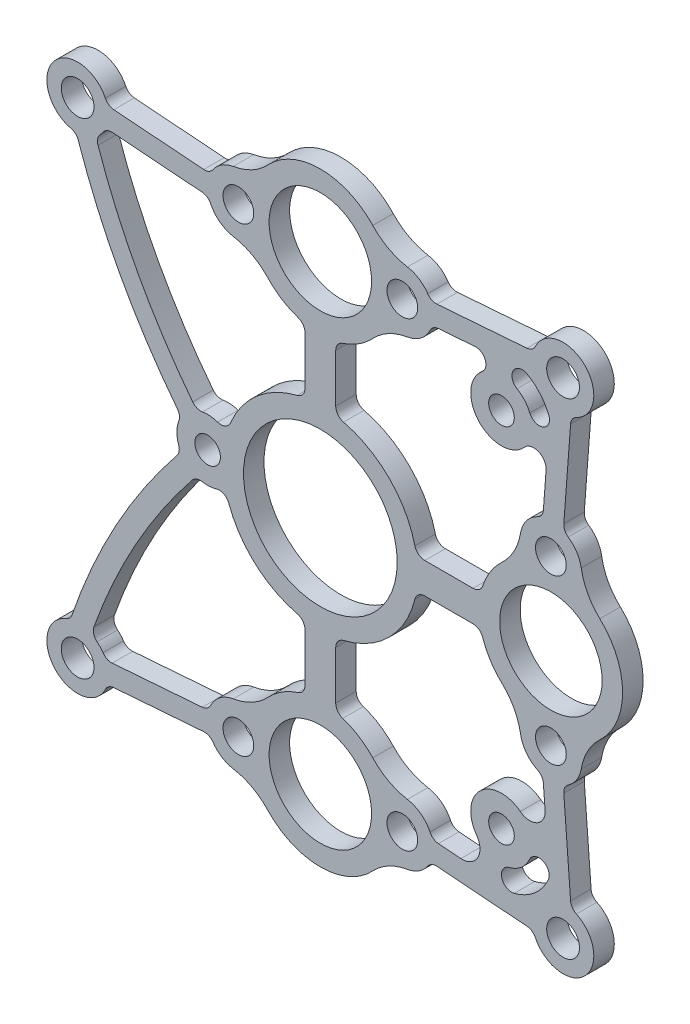
SolidWorks part; units mm, degrees
material "A2017"
ref_plane "正面" through (0, 0, 0) normal (0, 0, 1) x (1, 0, 0)
ref_plane "平面" through (0, 0, 0) normal (0, 1, 0) x (1, 0, 0)
ref_plane "右側面" through (0, 0, 0) normal (1, 0, 0) x (0, 0, -1)
sketch "ｽｹｯﾁ1" plane through (0, 0, 0) normal (0, 0, 1) x (1, 0, 0)
  line L0 (0, 29.5) -> (0, 22.5) construction
  line L1 (-8, 22.5) -> (8, 22.5) construction
  line L2 (29.5, 0) -> (22.5, 0) construction
  line L3 (22.5, 8) -> (22.5, -8) construction
  line L4 (0, -29.5) -> (0, -22.5) construction
  line L5 (8, -22.5) -> (-8, -22.5) construction
  line L6 (-29.5, 0) -> (-22.5, 0) construction
  line L7 (-22.5, -8) -> (-22.5, 8) construction
  circle A1 centre (23.6881, 23.6881) radius 3
  circle A2 centre (23.6881, 23.6881) radius 3
  circle A3 centre (22.5, 0) radius 5
  circle A5 centre (22.5, -8) radius 1.5
  circle A7 centre (0, 22.5) radius 5
  circle A8 centre (0, 22.5) radius 5
  circle A9 centre (0, 0) radius 7.5
  circle A10 centre (0, 0) radius 7.5
  circle A11 centre (8, 22.5) radius 1.5
  circle A12 centre (8, 22.5) radius 1.5
  circle A13 centre (-8, 22.5) radius 1.5
  circle A14 centre (-8, 22.5) radius 1.5
  circle A15 centre (-23.6881, -23.6881) radius 3
  circle A16 centre (-23.6881, -23.6881) radius 3
  circle A17 centre (-23.6881, 23.6881) radius 3
  circle A18 centre (-23.6881, 23.6881) radius 3
  circle A19 centre (23.6881, -23.6881) radius 3
  circle A20 centre (23.6881, -23.6881) radius 3
  circle A21 centre (22.5, 8) radius 1.5
  arc A23 (27.2784, 5.1154) -> (27.2784, -5.1154) centre (22.5, 0) cw
  arc A25 (27.2784, 5.1154) -> (25.458, 8.5) centre (31.3741, 9.5) cw
  arc A27 (27.2784, -5.1154) -> (25.458, -8.5) centre (31.3741, -9.5) ccw
  circle A42 centre (0, 0) radius 9.5
  circle A43 centre (-23.6881, 23.6881) radius 1.6
  circle A44 centre (-23.6881, -23.6881) radius 1.6
  circle A45 centre (23.6881, -23.6881) radius 1.6
  circle A46 centre (23.6881, 23.6881) radius 1.6
  circle A47 centre (-8, 22.5) radius 3 construction
  circle A48 centre (0, 22.5) radius 7 construction
  circle A49 centre (8, 22.5) radius 3 construction
  arc A50 (-5.1154, 27.2784) -> (5.1154, 27.2784) centre (0, 22.5) cw
  arc A51 (-5.1154, 27.2784) -> (-8.5, 25.458) centre (-9.5, 31.3741) cw
  arc A52 (5.1154, 27.2784) -> (8.5, 25.458) centre (9.5, 31.3741) ccw
  arc A53 (-8.5, 25.458) -> (-8.5, 19.542) centre (-8, 22.5) ccw
  arc A54 (8.5, 25.458) -> (8.5, 19.542) centre (8, 22.5) cw
  arc A55 (-5.1154, 17.7216) -> (-8.5, 19.542) centre (-9.5, 13.6259) ccw
  arc A56 (-5.1154, 17.7216) -> (5.1154, 17.7216) centre (0, 22.5) ccw
  arc A57 (5.1154, 17.7216) -> (8.5, 19.542) centre (9.5, 13.6259) cw
  arc A58 (25.458, 8.5) -> (19.542, 8.5) centre (22.5, 8) ccw
  arc A59 (25.458, -8.5) -> (19.542, -8.5) centre (22.5, -8) cw
  arc A60 (17.7216, 5.1154) -> (19.542, 8.5) centre (13.6259, 9.5) ccw
  arc A61 (17.7216, 5.1154) -> (17.7216, -5.1154) centre (22.5, 0) ccw
  arc A62 (17.7216, -5.1154) -> (19.542, -8.5) centre (13.6259, -9.5) cw
  circle A63 centre (22.5, 8) radius 3 construction
  circle A64 centre (22.5, 0) radius 7 construction
  circle A65 centre (22.5, -8) radius 3 construction
  circle A66 centre (0, -22.5) radius 5
  circle A67 centre (-8, -22.5) radius 1.5
  circle A68 centre (8, -22.5) radius 1.5
  arc A69 (5.1154, -27.2784) -> (-5.1154, -27.2784) centre (0, -22.5) cw
  arc A70 (5.1154, -27.2784) -> (8.5, -25.458) centre (9.5, -31.3741) cw
  arc A71 (-5.1154, -27.2784) -> (-8.5, -25.458) centre (-9.5, -31.3741) ccw
  arc A72 (8.5, -25.458) -> (8.5, -19.542) centre (8, -22.5) ccw
  arc A73 (-8.5, -25.458) -> (-8.5, -19.542) centre (-8, -22.5) cw
  arc A74 (5.1154, -17.7216) -> (8.5, -19.542) centre (9.5, -13.6259) ccw
  arc A75 (5.1154, -17.7216) -> (-5.1154, -17.7216) centre (0, -22.5) ccw
  arc A76 (-5.1154, -17.7216) -> (-8.5, -19.542) centre (-9.5, -13.6259) cw
  circle A77 centre (8, -22.5) radius 3 construction
  circle A78 centre (0, -22.5) radius 7 construction
  circle A79 centre (-8, -22.5) radius 3 construction
  circle A80 centre (-22.5, 0) radius 5 [skipped]
  circle A81 centre (-22.5, 8) radius 1.5 [skipped]
  circle A82 centre (-22.5, -8) radius 1.5 [skipped]
  arc A83 (-27.2784, -5.1154) -> (-27.2784, 5.1154) centre (-22.5, 0) cw [skipped]
  arc A84 (-27.2784, -5.1154) -> (-25.458, -8.5) centre (-31.3741, -9.5) cw [skipped]
  arc A85 (-27.2784, 5.1154) -> (-25.458, 8.5) centre (-31.3741, 9.5) ccw [skipped]
  arc A86 (-25.458, -8.5) -> (-19.542, -8.5) centre (-22.5, -8) ccw [skipped]
  arc A87 (-25.458, 8.5) -> (-19.542, 8.5) centre (-22.5, 8) cw [skipped]
  arc A88 (-17.7216, -5.1154) -> (-19.542, -8.5) centre (-13.6259, -9.5) ccw [skipped]
  arc A89 (-17.7216, -5.1154) -> (-17.7216, 5.1154) centre (-22.5, 0) ccw [skipped]
  arc A90 (-17.7216, 5.1154) -> (-19.542, 8.5) centre (-13.6259, 9.5) cw [skipped]
  circle A91 centre (-22.5, -8) radius 3 construction
  circle A92 centre (-22.5, 0) radius 7 construction
  circle A93 centre (-22.5, 8) radius 3 construction
  point P121 (0, 0)
  dimension "D15" = 19
  dimension "D16" = 2
  dimension "D17" = 3.2
  dimension "D18" = 14
  dimension "D19" = 6
  dimension "D20" = 6
  dimension "D1" = 0
  dimension "D3" = 4
  dimension "D4" = 0
  dimension "D5" = 0
  dimension "D6" = 0
  dimension "D7" = 0
  dimension "D8" = 0
  dimension "D9" = 0
  dimension "D10" = 0
extrude "ﾎﾞｽ - 押し出し1" add sketch "ｽｹｯﾁ1" against normal blind 2
sketch "ｽｹｯﾁ2" plane through (0, 0, 0) normal (0, 0, 1) x (1, 0, 0)
  circle A0 centre (-11, 0.25) radius 1.5 construction
  circle A1 centre (17.6777, 17.9277) radius 1.5 construction
  circle A2 centre (17.6777, -17.4277) radius 1.5 construction
  circle A3 centre (-11, 0.25) radius 3
  circle A4 centre (17.6777, 17.9277) radius 3
  circle A5 centre (17.6777, -17.4277) radius 3
  dimension "D1" = 3
  dimension "D2" = 6
extrude "ﾎﾞｽ - 押し出し2" add sketch "ｽｹｯﾁ2" against normal through all
hole_wizard "M3 ねじ穴1" positions "ｽｹｯﾁ3" profile "ｽｹｯﾁ4" tap size "M3" standard "JIS" end condition through all
sketch "ｽｹｯﾁ3" plane through (0, 0, 0) normal (0, 0, 1) x (1, 0, 0)
  point P0 (-11, 0.25)
  point P3 (17.6777, 17.9277)
  point P6 (17.6777, -17.4277)
sketch "ｽｹｯﾁ4" plane through (-11, 0.25, 0) normal (1, 0, 0) x (0, -1, 0)
  line L0 (0, 0) -> (0, 2)
  line L1 (0, 2) -> (1.25, 2)
  line L2 (1.25, 2) -> (1.25, 0)
  line L5 (1.25, 0) -> (0, 0)
  line L11 (0, -6.35) -> (0, 107.95) construction
  dimension "次ｻｰﾌｪｽまでのねじ下穴ﾄﾞﾘﾙ直径" = 2.5
  dimension "次ｻｰﾌｪｽまでのねじ下穴ﾄﾞﾘﾙの深さ" = 2
cosmetic thread "穴のねじ山1" parameters "D2"=3
cosmetic thread "穴のねじ山2" parameters "D2"=3
cosmetic thread "穴のねじ山3" parameters "D2"=3
sketch "ｽｹｯﾁ5" plane through (0, 0, 0) normal (0, 0, 1) x (1, 0, 0)
  line L0 (0, 22.5) -> (0, 0) construction
  line L1 (0, 22.5) -> (0, 0) construction
  line L2 (1.5, 22.5) -> (1.5, 0)
  line L3 (-1.5, 22.5) -> (-1.5, 0)
  line L4 (22.5, 0) -> (0, 0) construction
  line L5 (22.5, -1.5) -> (0, -1.5)
  line L6 (22.5, 1.5) -> (0, 1.5)
  line L7 (0, 0) -> (0, -22.5) construction
  line L8 (1.5, 0) -> (1.5, -22.5)
  line L9 (-1.5, 0) -> (-1.5, -22.5)
  arc A0 (1.5, 22.5) -> (-1.5, 22.5) centre (0, 22.5) ccw
  arc A1 (-1.5, 0) -> (1.5, 0) centre (0, 0) ccw
  arc A2 (22.5, -1.5) -> (22.5, 1.5) centre (22.5, 0) ccw
  arc A3 (0, 1.5) -> (0, -1.5) centre (0, 0) ccw
  arc A4 (1.5, 0) -> (-1.5, 0) centre (0, 0) ccw
  arc A5 (-1.5, -22.5) -> (1.5, -22.5) centre (0, -22.5) ccw
  arc A6 (5.1154, -17.7216) -> (-5.1154, -17.7216) centre (0, -22.5) ccw construction
  arc A7 (17.7216, 5.1154) -> (17.7216, -5.1154) centre (22.5, 0) ccw construction
  arc A8 (-5.1154, 17.7216) -> (5.1154, 17.7216) centre (0, 22.5) ccw construction
  arc A9 (-9.2456, -2.1836) -> (-9.1369, 2.6014) centre (0, 0) ccw construction
  arc A10 (5.1154, -17.7216) -> (-5.1154, -17.7216) centre (0, -22.5) ccw
  arc A11 (17.7216, 5.1154) -> (17.7216, -5.1154) centre (22.5, 0) ccw
  arc A12 (-5.1154, 17.7216) -> (5.1154, 17.7216) centre (0, 22.5) ccw
  arc A13 (-9.2456, -2.1836) -> (-9.1369, 2.6014) centre (0, 0) ccw
  point P4 (0, 11.25)
  point P12 (11.25, 0)
  point P17 (0, -11.25)
  arc M19 (-5.1154, 17.7216) -> (5.1154, 17.7216) centre (0, 22.5) ccw
  dimension "D1" = 3
extrude "ﾎﾞｽ - 押し出し3" add sketch "ｽｹｯﾁ5" against normal through all contours A13 L2 L3 M19 | A13 L5 A11 L6 | A13 L9 A10 L8
sketch "ｽｹｯﾁ6" plane through (0, 0, 0) normal (0, 0, 1) x (1, 0, 0)
  line L0 (8, 22.5) -> (23.6881, 23.6881) construction
  line L1 (7.9245, 23.4971) -> (23.6126, 24.6852)
  line L2 (8.0755, 21.5029) -> (23.7636, 22.6909)
  line L3 (22.5, 8) -> (23.6881, 23.6881) construction
  line L4 (21.5029, 8.0755) -> (22.6909, 23.7636)
  line L5 (23.4971, 7.9245) -> (24.6852, 23.6126)
  line L6 (0, 0) -> (29.5, 0) construction
  line L7 (8, -22.5) -> (23.6881, -23.6881) construction
  line L8 (7.9245, -23.4971) -> (23.6126, -24.6852)
  line L9 (8.0755, -21.5029) -> (23.7636, -22.6909)
  line L10 (22.5, -8) -> (23.6881, -23.6881) construction
  line L11 (21.5029, -8.0755) -> (22.6909, -23.7636)
  line L12 (23.4971, -7.9245) -> (24.6852, -23.6126)
  arc A0 (7.9245, 23.4971) -> (8.0755, 21.5029) centre (8, 22.5) ccw
  arc A1 (23.7636, 22.6909) -> (23.6126, 24.6852) centre (23.6881, 23.6881) ccw
  arc A2 (21.5029, 8.0755) -> (23.4971, 7.9245) centre (22.5, 8) ccw
  arc A3 (24.6852, 23.6126) -> (22.6909, 23.7636) centre (23.6881, 23.6881) ccw
  arc A5 (8.5, 19.542) -> (8.5, 25.458) centre (8, 22.5) ccw construction
  arc A6 (25.458, 8.5) -> (19.542, 8.5) centre (22.5, 8) ccw construction
  circle A7 centre (23.6881, 23.6881) radius 3 construction
  arc A8 (8.5, 19.542) -> (8.5, 25.458) centre (8, 22.5) ccw
  arc A9 (25.458, 8.5) -> (19.542, 8.5) centre (22.5, 8) ccw
  circle A10 centre (23.6881, 23.6881) radius 3
  arc A11 (7.9245, -23.4971) -> (8.0755, -21.5029) centre (8, -22.5) cw
  arc A12 (23.7636, -22.6909) -> (23.6126, -24.6852) centre (23.6881, -23.6881) cw
  arc A13 (21.5029, -8.0755) -> (23.4971, -7.9245) centre (22.5, -8) cw
  arc A14 (24.6852, -23.6126) -> (22.6909, -23.7636) centre (23.6881, -23.6881) cw
  circle A15 centre (23.6881, -23.6881) radius 3
  arc A16 (25.458, -8.5) -> (19.542, -8.5) centre (22.5, -8) cw
  arc A17 (8.5, -19.542) -> (8.5, -25.458) centre (8, -22.5) cw
  arc A18 (27.2784, -5.1154) -> (27.2784, 5.1154) centre (22.5, 0) ccw construction
  point P4 (15.844, 23.094)
  point P12 (23.094, 15.844)
  point P33 (15.844, -23.094)
  point P40 (23.094, -15.844)
  circle M10 centre (23.6881, 23.6881) radius 3
  dimension "D1" = 2
extrude "ﾎﾞｽ - 押し出し4" add sketch "ｽｹｯﾁ6" against normal through all contours L12 A16 L11 A15 | L9 A17 L8 A15 | A9 L5 L4 M10 | A8 L2 L1 M10
sketch "ｽｹｯﾁ7" plane through (0, 0, 0) normal (0, 0, 1) x (1, 0, 0)
  line L0 (10.8959, 21.7164) -> (20.9432, 22.4773) construction
  line L1 (23.6881, 23.6881) -> (17.6777, 17.9277) construction
  line L2 (21.7164, 10.8959) -> (22.4773, 20.9432) construction
  line L3 (20.823, 15.1286) -> (17.6777, 17.9277) construction
  line L4 (17.6777, 17.9277) -> (15.1608, 21.0366) construction
  line L5 (15.1608, 21.0366) -> (20.823, 15.1286) construction
  line L6 (21.7164, 10.8959) -> (22.4773, 20.9432)
  line L7 (10.8959, 21.7164) -> (20.9432, 22.4773)
  line L8 (17.6777, -17.4277) -> (23.6881, -23.6881) construction
  line L9 (10.8959, -21.7164) -> (20.9432, -22.4773) construction
  line L10 (21.7164, -10.8959) -> (22.4773, -20.9432) construction
  line L11 (10.8959, -21.7164) -> (20.9432, -22.4773)
  line L12 (21.7164, -10.8959) -> (22.4773, -20.9432)
  line L13 (13.845, -20.2029) -> (17.6777, -17.4277) construction
  line L14 (17.6777, -17.4277) -> (20.4376, -13.8734) construction
  line L15 (20.4376, -13.8734) -> (13.845, -20.2029) construction
  circle A0 centre (15.1608, 21.0366) radius 1
  circle A1 centre (17.6777, 17.9277) radius 3 construction
  circle A2 centre (17.6777, 17.9277) radius 3
  circle A3 centre (20.823, 15.1286) radius 1.2105
  arc A4 (20.9432, 22.4773) -> (22.4773, 20.9432) centre (23.6881, 23.6881) ccw construction
  arc A5 (20.9432, 22.4773) -> (22.4773, 20.9432) centre (23.6881, 23.6881) ccw
  arc A6 (22.4773, -20.9432) -> (20.9432, -22.4773) centre (23.6881, -23.6881) ccw construction
  circle A7 centre (17.6777, -17.4277) radius 3 construction
  arc A8 (22.4773, -20.9432) -> (20.9432, -22.4773) centre (23.6881, -23.6881) ccw
  circle A9 centre (17.6777, -17.4277) radius 3
  circle A10 centre (20.4376, -13.8734) radius 1.5
  circle A11 centre (13.845, -20.2029) radius 1.732
  dimension "D1" = 2
  dimension "D2" = 3
extrude "ﾎﾞｽ - 押し出し5" add sketch "ｽｹｯﾁ7" against normal through all contours A11 L11 A8 L12 A10 A9 | A5 L7 A0 A2 A3 L6
sketch "ｽｹｯﾁ8" plane through (0, 0, 0) normal (0, 0, 1) x (1, 0, 0)
  line L0 (-8, 22.5) -> (-23.6881, 23.6881) construction
  line L1 (-8.0755, 21.5029) -> (-23.7636, 22.6909)
  line L2 (-7.9245, 23.4971) -> (-23.6126, 24.6852)
  line L3 (-8, -22.5) -> (-23.6881, -23.6881) construction
  line L4 (-7.9245, -23.4971) -> (-23.6126, -24.6852)
  line L5 (-8.0755, -21.5029) -> (-23.7636, -22.6909)
  line L6 (-11, 0.25) -> (22.5, 0) construction
  line L18 (10.7448, -23.7107) -> (20.7922, -24.4716)
  line L19 (24.4716, -20.7922) -> (23.7107, -10.7448)
  line L20 (23.7107, 10.7448) -> (24.4716, 20.7922)
  line L21 (20.7922, 24.4716) -> (10.7448, 23.7107)
  line L22 (-1.5, 15.6626) -> (-1.5, 9.3808)
  line L23 (-1.5, -9.3808) -> (-1.5, -15.6626)
  line L24 (10.7448, -23.7107) -> (20.7922, -24.4716)
  line L25 (24.4716, -20.7922) -> (23.7107, -10.7448)
  line L26 (23.7107, 10.7448) -> (24.4716, 20.7922)
  line L27 (20.7922, 24.4716) -> (10.7448, 23.7107)
  line L28 (-1.5, 15.6626) -> (-1.5, 9.3808)
  line L29 (-1.5, -9.3808) -> (-1.5, -15.6626)
  arc A0 (-8.0755, 21.5029) -> (-7.9245, 23.4971) centre (-8, 22.5) ccw
  arc A1 (-23.6126, 24.6852) -> (-23.7636, 22.6909) centre (-23.6881, 23.6881) ccw
  arc A2 (-7.9245, -23.4971) -> (-8.0755, -21.5029) centre (-8, -22.5) ccw
  arc A3 (-23.7636, -22.6909) -> (-23.6126, -24.6852) centre (-23.6881, -23.6881) ccw
  arc A8 (-23.6881, 23.6881) -> (-11, 0.25) centre (34.1027, 39.8195) ccw construction
  circle A9 centre (-23.6881, -23.6881) radius 3 construction
  circle A10 centre (-23.6881, 23.6881) radius 3 construction
  circle A11 centre (-23.6881, -23.6881) radius 3
  circle A12 centre (-23.6881, 23.6881) radius 3
  arc A13 (-24.6513, 23.4192) -> (-11.7517, -0.4095) centre (34.1027, 39.8195) ccw
  arc A14 (-22.7249, 23.9569) -> (-10.2483, 0.9095) centre (34.1027, 39.8195) ccw
  arc A15 (-22.7249, 23.9569) -> (-24.6513, 23.4192) centre (-23.6881, 23.6881) ccw
  arc A16 (-11.7517, -0.4095) -> (-10.2483, 0.9095) centre (-11, 0.25) ccw
  arc A17 (-24.0365, -22.9961) -> (-11, 0.25) centre (33.5072, -39.9882) cw construction
  arc A18 (-24.9955, -22.7129) -> (-11.7418, 0.9206) centre (33.5072, -39.9882) cw
  arc A19 (-23.0774, -23.2793) -> (-10.2582, -0.4206) centre (33.5072, -39.9882) cw
  arc A20 (-23.0774, -23.2793) -> (-24.9955, -22.7129) centre (-24.0365, -22.9961) cw
  arc A21 (-11.7418, 0.9206) -> (-10.2582, -0.4206) centre (-11, 0.25) cw
  arc A33 (8.5, -25.458) -> (10.7448, -23.7107) centre (8, -22.5) ccw
  arc A34 (20.7922, -24.4716) -> (24.4716, -20.7922) centre (23.6881, -23.6881) ccw
  arc A35 (23.7107, -10.7448) -> (25.458, -8.5) centre (22.5, -8) ccw
  arc A36 (27.2784, -5.1154) -> (25.458, -8.5) centre (31.3741, -9.5) ccw
  arc A37 (27.2784, -5.1154) -> (27.2784, 5.1154) centre (22.5, 0) ccw
  arc A38 (25.458, 8.5) -> (27.2784, 5.1154) centre (31.3741, 9.5) ccw
  arc A39 (25.458, 8.5) -> (23.7107, 10.7448) centre (22.5, 8) ccw
  arc A40 (24.4716, 20.7922) -> (20.7922, 24.4716) centre (23.6881, 23.6881) ccw
  arc A41 (10.7448, 23.7107) -> (8.5, 25.458) centre (8, 22.5) ccw
  arc A42 (5.1154, 27.2784) -> (8.5, 25.458) centre (9.5, 31.3741) ccw
  arc A43 (5.1154, 27.2784) -> (-5.1154, 27.2784) centre (0, 22.5) ccw
  arc A44 (-8.5, 25.458) -> (-5.1154, 27.2784) centre (-9.5, 31.3741) ccw
  arc A45 (-8.5, 25.458) -> (-8.5, 19.542) centre (-8, 22.5) ccw
  arc A46 (-5.1154, 17.7216) -> (-8.5, 19.542) centre (-9.5, 13.6259) ccw
  arc A47 (-5.1154, 17.7216) -> (-1.5, 15.6626) centre (0, 22.5) ccw
  arc A48 (-1.5, 9.3808) -> (-9.1369, 2.6014) centre (0, 0) ccw
  arc A49 (-9.1369, 2.6014) -> (-9.2456, -2.1836) centre (-11, 0.25) ccw
  arc A50 (-9.2456, -2.1836) -> (-1.5, -9.3808) centre (0, 0) ccw
  arc A51 (-1.5, -15.6626) -> (-5.1154, -17.7216) centre (0, -22.5) ccw
  arc A52 (-8.5, -19.542) -> (-5.1154, -17.7216) centre (-9.5, -13.6259) ccw
  arc A53 (-8.5, -19.542) -> (-8.5, -25.458) centre (-8, -22.5) ccw
  arc A54 (-5.1154, -27.2784) -> (-8.5, -25.458) centre (-9.5, -31.3741) ccw
  arc A55 (-5.1154, -27.2784) -> (5.1154, -27.2784) centre (0, -22.5) ccw
  arc A56 (8.5, -25.458) -> (5.1154, -27.2784) centre (9.5, -31.3741) ccw
  arc A57 (8.5, -25.458) -> (10.7448, -23.7107) centre (8, -22.5) ccw
  arc A58 (20.7922, -24.4716) -> (24.4716, -20.7922) centre (23.6881, -23.6881) ccw
  arc A59 (23.7107, -10.7448) -> (25.458, -8.5) centre (22.5, -8) ccw
  arc A60 (27.2784, -5.1154) -> (25.458, -8.5) centre (31.3741, -9.5) ccw
  arc A61 (27.2784, -5.1154) -> (27.2784, 5.1154) centre (22.5, 0) ccw
  arc A62 (25.458, 8.5) -> (27.2784, 5.1154) centre (31.3741, 9.5) ccw
  arc A63 (25.458, 8.5) -> (23.7107, 10.7448) centre (22.5, 8) ccw
  arc A64 (24.4716, 20.7922) -> (20.7922, 24.4716) centre (23.6881, 23.6881) ccw
  arc A65 (10.7448, 23.7107) -> (8.5, 25.458) centre (8, 22.5) ccw
  arc A66 (5.1154, 27.2784) -> (8.5, 25.458) centre (9.5, 31.3741) ccw
  arc A67 (5.1154, 27.2784) -> (-5.1154, 27.2784) centre (0, 22.5) ccw
  arc A68 (-8.5, 25.458) -> (-5.1154, 27.2784) centre (-9.5, 31.3741) ccw
  arc A69 (-8.5, 25.458) -> (-8.5, 19.542) centre (-8, 22.5) ccw
  arc A70 (-5.1154, 17.7216) -> (-8.5, 19.542) centre (-9.5, 13.6259) ccw
  arc A71 (-5.1154, 17.7216) -> (-1.5, 15.6626) centre (0, 22.5) ccw
  arc A72 (-1.5, 9.3808) -> (-9.1369, 2.6014) centre (0, 0) ccw
  arc A73 (-9.1369, 2.6014) -> (-9.2456, -2.1836) centre (-11, 0.25) ccw
  arc A74 (-9.2456, -2.1836) -> (-1.5, -9.3808) centre (0, 0) ccw
  arc A75 (-1.5, -15.6626) -> (-5.1154, -17.7216) centre (0, -22.5) ccw
  arc A76 (-8.5, -19.542) -> (-5.1154, -17.7216) centre (-9.5, -13.6259) ccw
  arc A77 (-8.5, -19.542) -> (-8.5, -25.458) centre (-8, -22.5) ccw
  arc A78 (-5.1154, -27.2784) -> (-8.5, -25.458) centre (-9.5, -31.3741) ccw
  arc A79 (-5.1154, -27.2784) -> (5.1154, -27.2784) centre (0, -22.5) ccw
  arc A80 (8.5, -25.458) -> (5.1154, -27.2784) centre (9.5, -31.3741) ccw
  point P4 (-15.844, 23.094)
  point P9 (-15.844, -23.094)
  point P18 (-18.6619, 11.2556)
  point P27 (-18.8253, -10.64)
  dimension "D3" = 60
  dimension "D1" = 2
  dimension "D2" = 0
extrude "ﾎﾞｽ - 押し出し6" add sketch "ｽｹｯﾁ8" against normal through all
sketch "ｽｹｯﾁ9" plane through (0, 0, 0) normal (0, 0, 1) x (1, 0, 0)
  line L0 (10.8959, 21.7164) -> (15.0853, 22.0337) construction
  line L1 (15.0853, 22.0337) -> (22.603, 22.603) construction
  line L2 (22.603, 22.603) -> (22.0198, 14.9011) construction
  line L3 (21.7164, 10.8959) -> (22.0301, 15.0372) construction
  line L4 (22.0198, 14.9011) -> (21.7164, 10.8959) construction
  line L5 (13.7142, -21.9299) -> (22.603, -22.603) construction
  line L6 (22.603, -22.603) -> (21.9334, -13.7602) construction
  line L7 (21.7164, -10.8959) -> (21.9334, -13.7602) construction
  line L8 (10.8959, -21.7164) -> (13.7142, -21.9299) construction
  arc A0 (19.6977, 21.3802) -> (21.3638, 19.4811) centre (17.6777, 17.9277) cw construction
  arc A1 (22.2853, 19.8694) -> (20.2027, 22.2433) centre (17.6777, 17.9277) ccw
  arc A2 (20.4422, 19.0927) -> (19.1927, 20.517) centre (17.6777, 17.9277) ccw
  arc A3 (20.4422, 19.0927) -> (22.2853, 19.8694) centre (21.3638, 19.4811) ccw
  arc A4 (20.2027, 22.2433) -> (19.1927, 20.517) centre (19.6977, 21.3802) ccw
  circle A5 centre (17.6777, 17.9277) radius 3 construction
  circle A6 centre (17.6777, -17.4277) radius 3 construction
  arc A7 (21.3315, -19.0555) -> (18.671, -21.3024) centre (17.6777, -17.4277) cw construction
  arc A8 (18.9193, -22.2711) -> (22.245, -19.4624) centre (17.6777, -17.4277) ccw
  arc A9 (18.4227, -20.3337) -> (20.4181, -18.6485) centre (17.6777, -17.4277) ccw
  arc A10 (18.4227, -20.3337) -> (18.9193, -22.2711) centre (18.671, -21.3024) ccw
  arc A11 (22.245, -19.4624) -> (20.4181, -18.6485) centre (21.3315, -19.0555) ccw
  point P4 (20.6846, 20.5656)
  point P37 (20.2586, -20.4837)
  dimension "D1" = 2
  dimension "D2" = 2
extrude "ｶｯﾄ - 押し出し1" cut sketch "ｽｹｯﾁ9" against normal up to surface (2 mm away) up to face at (-10.4688, -14.7595, -2)
fillet "ﾌｨﾚｯﾄ1" radius 1 42 edges at (1.5, -15.6626, -1) (1.5, -9.3808, -1) (9.3808, -1.5, -1) (15.6626, -1.5, -1) (21.7164, -10.8959, -1) (10.8959, -21.7164, -1) (21.7164, 10.8959, -1) (15.6626, 1.5, -1) (9.3808, 1.5, -1) (1.5, 9.3808, -1) (1.5, 15.6626, -1) (10.8959, 21.7164, -1) (-20.7922, -24.4716, -1) (-10.7448, -23.7107, -1) (10.7448, -23.7107, -1) (20.7922, -24.4716, -1) (24.4716, -20.7922, -1) (23.7107, -10.7448, -1) (23.7107, 10.7448, -1) (24.4716, 20.7922, -1) (20.7922, 24.4716, -1) (10.7448, 23.7107, -1) (-10.7448, 23.7107, -1) (-23.8205, 20.691, -1) (-13.5819, 1.7777, -1) (-13.6044, -1.239, -1) (-24.3865, -20.7705, -1) (-1.5, 15.6626, -1) (-1.5, 9.3808, -1) (-9.1369, 2.6014, -1) (-9.2456, -2.1836, -1) (-12.0474, 3.0612, -1) (-21.9068, 21.2741, -1) (-20.9432, 22.4773, -1) (-10.8959, 21.7164, -1) (-22.3541, -21.001, -1) (-12.0892, -2.5453, -1) (-1.5, -9.3808, -1) (-1.5, -15.6626, -1) (-10.8959, -21.7164, -1) (-20.9432, -22.4773, -1) (-20.7922, 24.4716, -1)
